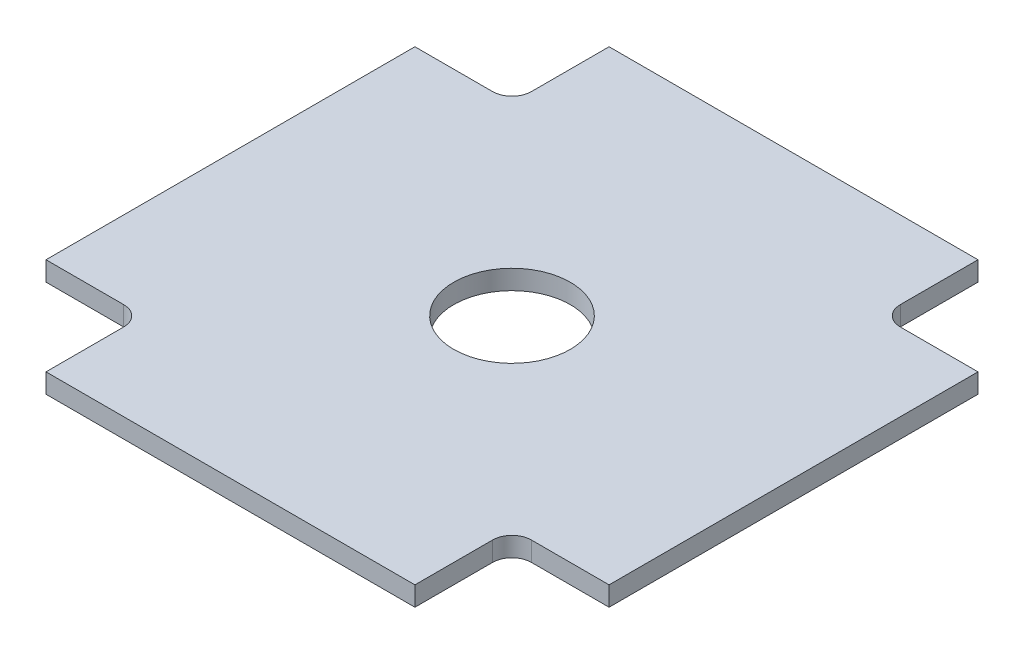
SolidWorks part; units mm, degrees
material "A286 Iron Base Superalloy"
ref_plane "Front Plane" through (0, 0, 0) normal (0, 0, 1) x (1, 0, 0)
ref_plane "Top Plane" through (0, 0, 0) normal (0, 1, 0) x (1, 0, 0)
ref_plane "Right Plane" through (0, 0, 0) normal (1, 0, 0) x (0, 0, -1)
sketch "Sketch2" plane through (0, 0, 0) normal (0, 1, 0) x (1, 0, 0)
  line L0 (14.5, 0) -> (14.5, 29) construction
  line L5 (0, 24) -> (5, 24)
  line L6 (5, 24) -> (5, 29)
  line L7 (24, 29) -> (24, 24)
  line L8 (24, 24) -> (29, 24)
  line L9 (29, 5) -> (24, 5)
  line L10 (24, 5) -> (24, 0)
  line L11 (5, 0) -> (5, 5)
  line L12 (5, 5) -> (0, 5)
  line L13 (5, 0) -> (24, 0)
  line L14 (29, 24) -> (29, 5)
  line L15 (5, 29) -> (24, 29)
  line L16 (0, 24) -> (0, 5)
  circle A0 centre (14.5, 14.5) radius 3
  point P0 (0, 0)
  point P24 (14.5, 14.5)
  dimension "D3" = 6
  dimension "D2" = 14.5
  dimension "D1" = 19
  dimension "D4" = 5
  dimension "D5" = 5
  dimension "D6" = 4
extrude "Boss-Extrude1" add sketch "Sketch2" along normal blind 1
fillet "Fillet1" radius 1 4 edges at (24, 0.5, -5) (24, 0.5, -24) (5, 0.5, -24) (5, 0.5, -5)
